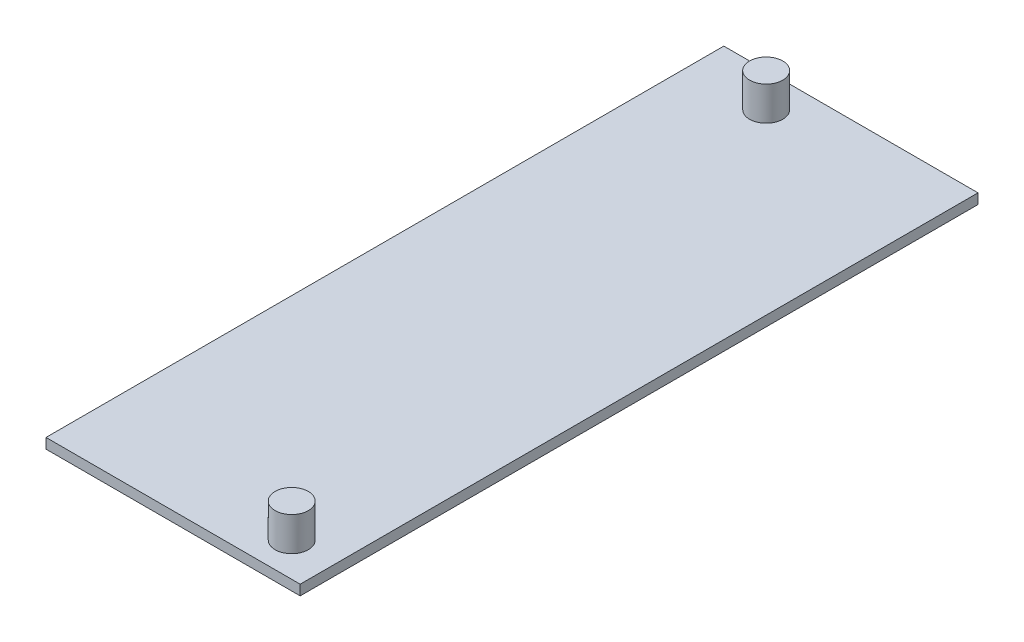
SolidWorks part; units mm, degrees
ref_plane "Front Plane" through (0, 0, 0) normal (0, 0, 1) x (1, 0, 0)
ref_plane "Top Plane" through (0, 0, 0) normal (0, 1, 0) x (1, 0, 0)
ref_plane "Right Plane" through (0, 0, 0) normal (1, 0, 0) x (0, 0, -1)
sketch "Sketch1" plane through (0, 0, 0) normal (0, 0, 1) x (1, 0, 0)
  line L1 (0, 0) -> (75, 0)
  line L2 (0, 0) -> (0, 3)
  line L3 (0, 3) -> (75, 3)
  line L4 (75, 0) -> (75, 3)
  dimension "D1" = 3
  dimension "D2" = 75
extrude "Boss-Extrude1" add sketch "Sketch1" along normal blind 200
sketch "Sketch2" plane through (0, 3, 0) normal (0, 1, 0) x (1, 0, 0)
  line L1 (225, 0) -> (0, 0)
  line L2 (225, 0) -> (225, -200)
  line L3 (225, -200) -> (0, -200)
  line L4 (0, 0) -> (0, -200)
  line L5 (212.5, -200) -> (12.5, -200)
  line L6 (212.5, -200) -> (212.5, 0)
  line L7 (212.5, 0) -> (12.5, 0)
  line L8 (12.5, -200) -> (12.5, 0)
  line L9 (75, -200) -> (0, -200) construction
  line L10 (75, 0) -> (0, 0) construction
  line L11 (75, -200) -> (75, 0) construction
  circle A0 centre (202.5, -190) radius 4.9
  circle A1 centre (162.5, -10) radius 4.9
  circle A2 centre (122.5, -190) radius 4.9
  circle A3 centre (82.5, -10) radius 4.9
  circle A4 centre (62.5, -190) radius 4.9
  circle A5 centre (22.5, -10) radius 4.9
  dimension "D4" = 10
  dimension "D5" = 10
  dimension "D6" = 9.8
  dimension "D7" = 9.8
  dimension "D8" = 10
  dimension "D9" = 40
  dimension "D11" = 10
  dimension "D12" = 10
  dimension "D13" = 80
  dimension "D14" = 80
  dimension "D15" = 10
  dimension "D16" = 10
  dimension "D17" = 60
  dimension "D18" = 60
  dimension "D19" = 9.8
  dimension "D20" = 9.8
  dimension "D21" = 9.8
  dimension "D22" = 9.8
  dimension "D1" = 225
  dimension "D2" = 12.5
  dimension "D3" = 12.5
  dimension "D10" = 150
extrude "Boss-Extrude2" add sketch "Sketch2" along normal blind 10 contours A4 | A5
sketch "Sketch5" plane through (0, 0, 0) normal (0, -1, 0) x (1, 0, 0)
  line L0 (45, 180) -> (50, 180)
  line L1 (45, 180) -> (45, 150)
  line L2 (45, 150) -> (50, 150)
  line L3 (50, 180) -> (50, 150)
  line L4 (0, 200) -> (75, 200) construction
  line L5 (0, 200) -> (0, 0) construction
  line L6 (45, 130) -> (50, 130)
  line L7 (45, 130) -> (45, 100)
  line L8 (45, 100) -> (50, 100)
  line L9 (50, 130) -> (50, 100)
  line L10 (45, 80) -> (50, 80)
  line L11 (45, 80) -> (45, 50)
  line L12 (45, 50) -> (50, 50)
  line L13 (50, 80) -> (50, 50)
  line L14 (45, 30) -> (50, 30)
  line L15 (45, 30) -> (45, 0)
  line L16 (45, 0) -> (50, 0)
  line L17 (50, 30) -> (50, 0)
  point P4 (47.5, 180)
  dimension "D1" = 5
  dimension "D2" = 30
  dimension "D3" = 20
  dimension "D4" = 47.5
  dimension "D5" = 4
extrude "Cut-Extrude2" cut sketch "Sketch5" against normal blind 1
